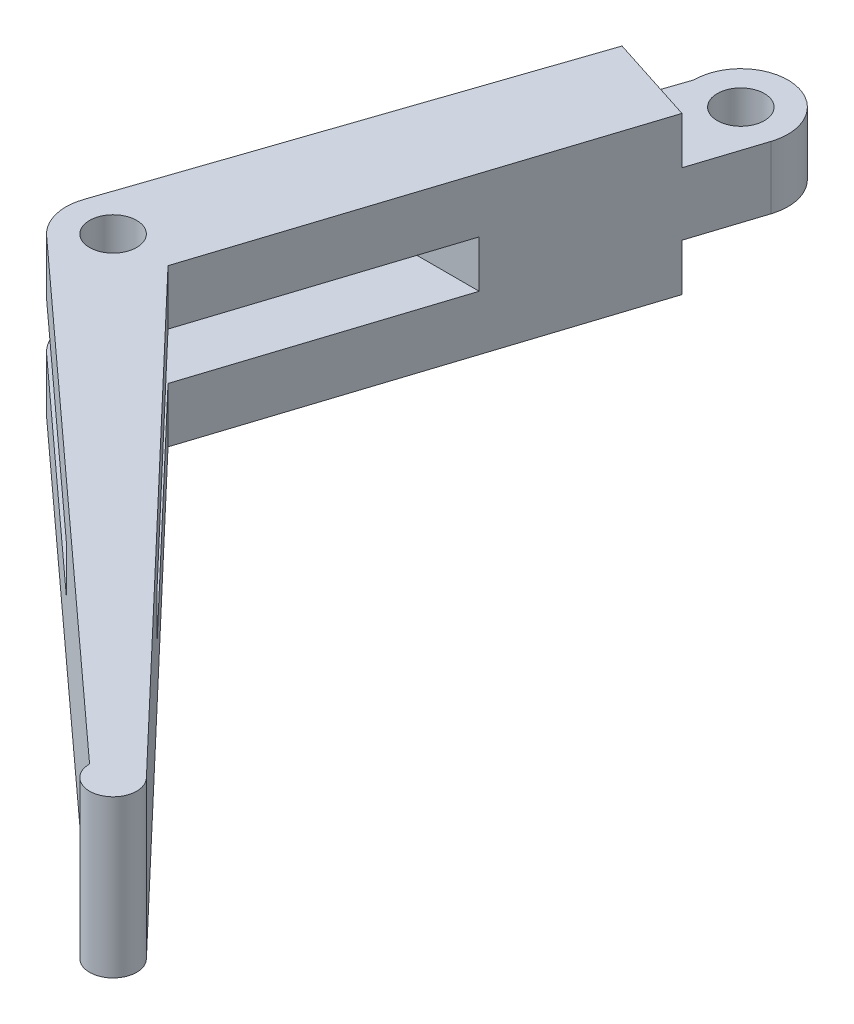
SolidWorks part; units mm, degrees
ref_plane "Alzado" through (0, 0, 0) normal (0, 0, 1) x (1, 0, 0)
ref_plane "Planta" through (0, 0, 0) normal (0, 1, 0) x (1, 0, 0)
ref_plane "Vista lateral" through (0, 0, 0) normal (1, 0, 0) x (0, 0, -1)
sketch "Croquis1" plane through (0, 0, 0) normal (0, 1, 0) x (1, 0, 0)
  line L0 (0, 0) -> (10, 30) construction
  line L1 (0, 0) -> (30, -30) construction
  line L2 (28.5, -30) -> (-2.0195, -2.2185)
  line L3 (3.5, 0) -> (31.0862, -28.9655)
  line L4 (7, 30) -> (-2.8413, 0.963)
  line L5 (3.5, 0) -> (12.8558, 29.0812)
  arc A0 (28.5, -30) -> (31.0862, -28.9655) centre (30, -30) ccw
  arc A1 (-2.8413, 0.963) -> (-2.0195, -2.2185) centre (0, 0) ccw
  arc A2 (12.8558, 29.0812) -> (7, 30) centre (10, 30) ccw
  circle A3 centre (10, 30) radius 1.5
  circle A4 centre (0, 0) radius 1.5
  dimension "D5" = 6
  dimension "D6" = 6
  dimension "D7" = 3
  dimension "D8" = 3
  dimension "D9" = 3
  dimension "D1" = 10
  dimension "D2" = 30
  dimension "D3" = 30
  dimension "D4" = 30
extrude "Saliente-Extruir1" add sketch "Croquis1" along normal mid plane 10
sketch "Croquis2" plane through (3.1717, 0, 1.0204) normal (0.9519, 0, 0.3063) x (0.3063, 0, -0.9519)
  line L1 (27.099, -2) -> (34.621, -2)
  line L3 (27.099, 2) -> (34.621, 2)
  line L7 (34.621, -5) -> (34.621, 5) construction
  line L9 (27.099, 2) -> (34.621, 2)
  line L10 (27.099, 2) -> (27.099, 5)
  line L11 (27.099, 5) -> (34.621, 5)
  line L12 (34.621, 2) -> (34.621, 5)
  line L13 (27.099, -2) -> (34.621, -2)
  line L14 (27.099, -2) -> (27.099, -5)
  line L15 (27.099, -5) -> (34.621, -5)
  line L16 (34.621, -2) -> (34.621, -5)
  line M6 (31.621, -5) -> (31.621, 5)
  dimension "D1" = 2
  dimension "D2" = 2
extrude "Cortar-Extruir1" cut sketch "Croquis2" against normal through all both and the other way through all contours L3 L12 L11 M6 | L16 L1 L15 M6
sketch "Croquis3" plane through (0, 0, 0) normal (1, 0, 0) x (0, 0, -1)
  line L1 (15, -1.5) -> (-15, -1.5)
  line L2 (15, -1.5) -> (15, 1.5)
  line L3 (15, 1.5) -> (-15, 1.5)
  line L4 (-15, -1.5) -> (-15, 1.5)
  line L5 (15, -1.5) -> (-15, 1.5) construction
  line L6 (15, 1.5) -> (-15, -1.5) construction
  point P0 (0, 0)
  dimension "D1" = 3
  dimension "D2" = 30
extrude "Cortar-Extruir2" cut sketch "Croquis3" against normal through all both and the other way through all
